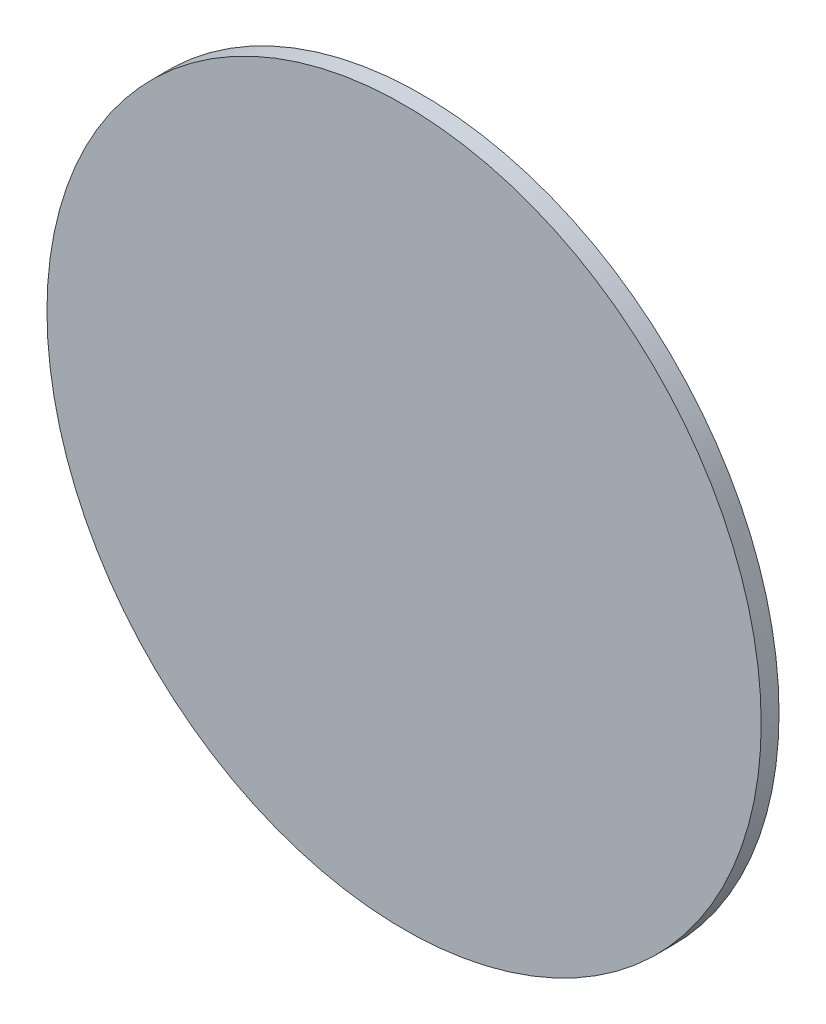
SolidWorks part; units mm, degrees
ref_plane "Front Plane" through (0, 0, 0) normal (0, 0, 1) x (1, 0, 0)
ref_plane "Top Plane" through (0, 0, 0) normal (0, 1, 0) x (1, 0, 0)
ref_plane "Right Plane" through (0, 0, 0) normal (1, 0, 0) x (0, 0, -1)
sketch "Sketch13" plane through (0, 0, 0) normal (0, 0, 1) x (1, 0, 0)
  circle A0 centre (0, 0) radius 50.8
  dimension "D1" = 101.6
extrude "Boss-Extrude2" add sketch "Sketch13" along normal blind 2.54 contours A0
